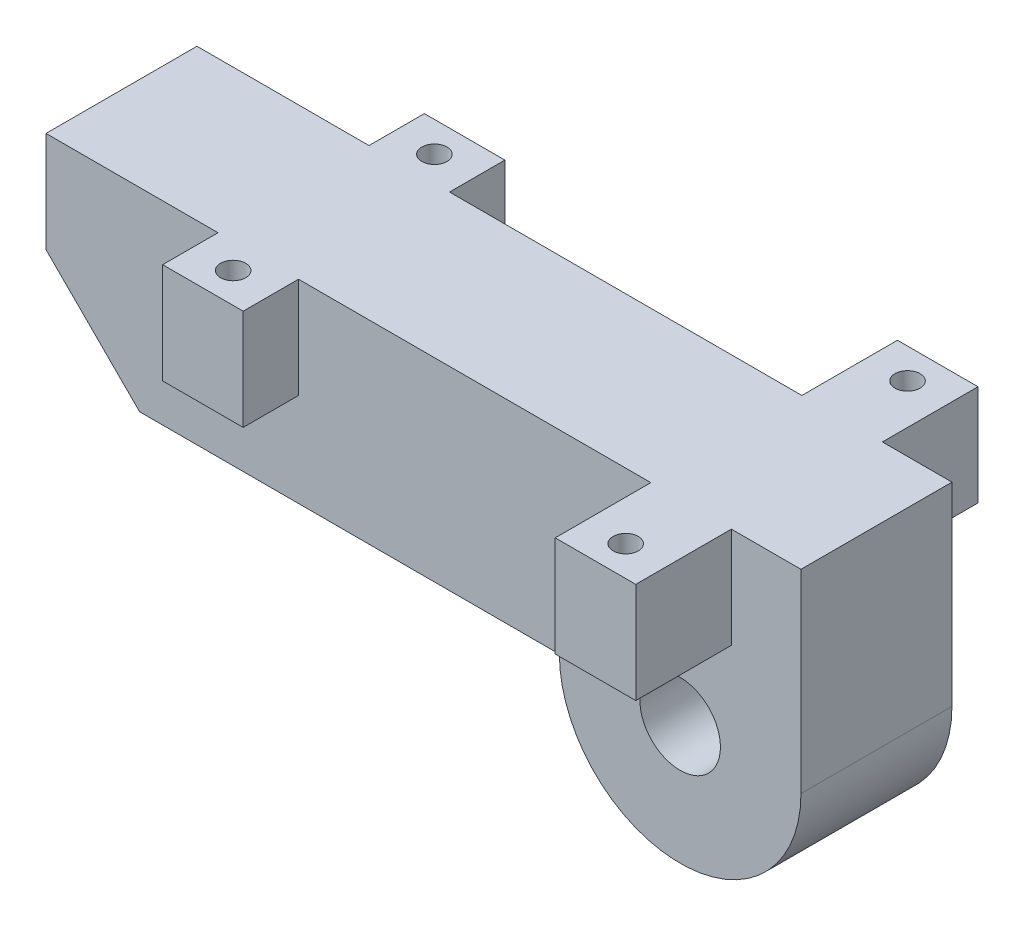
SolidWorks part; units mm, degrees
material "6061 合金"
ref_plane "前视基准面" through (0, 0, 0) normal (0, 0, 1) x (1, 0, 0)
ref_plane "上视基准面" through (0, 0, 0) normal (0, 1, 0) x (1, 0, 0)
ref_plane "右视基准面" through (0, 0, 0) normal (1, 0, 0) x (0, 0, -1)
sketch "草图2" plane through (0, 0, 0) normal (0, 1, 0) x (1, 0, 0)
  line L0 (-16.4121, -13) -> (-16.4121, 13) construction
  line L1 (37.5, 7.5) -> (30.5879, 7.5)
  line L2 (37.5, 7.5) -> (37.5, -7.5)
  line L3 (37.5, -7.5) -> (30.5879, -7.5)
  line L4 (-37.5, 7.5) -> (-37.5, -7.5)
  line L5 (37.5, 7.5) -> (-37.5, -7.5) construction
  line L6 (37.5, -7.5) -> (-37.5, 7.5) construction
  line L7 (-20.4121, 13) -> (-12.4121, 13)
  line L8 (-20.4121, 13) -> (-20.4121, 7.5)
  line L9 (-20.4121, -13) -> (-12.4121, -13)
  line L10 (-12.4121, 13) -> (-12.4121, 7.5)
  line L11 (22.5879, 17) -> (30.5879, 17)
  line L12 (22.5879, 17) -> (22.5879, 7.5)
  line L13 (22.5879, -17) -> (30.5879, -17)
  line L14 (30.5879, 17) -> (30.5879, 7.5)
  line L15 (-20.4121, -7.5) -> (-20.4121, -13)
  line L16 (-12.4121, -7.5) -> (-12.4121, -13)
  line L17 (-20.4121, -7.5) -> (-37.5, -7.5)
  line L18 (-20.4121, 7.5) -> (-37.5, 7.5)
  line L19 (22.5879, 7.5) -> (-12.4121, 7.5)
  line L20 (22.5879, -7.5) -> (22.5879, -17)
  line L21 (30.5879, -7.5) -> (30.5879, -17)
  line L22 (22.5879, -7.5) -> (-12.4121, -7.5)
  line L23 (-20.4121, 7.5) -> (-20.4121, -7.5) construction
  line L24 (-12.4121, 7.5) -> (-12.4121, -7.5) construction
  line L25 (22.5879, 7.5) -> (22.5879, -7.5) construction
  line L26 (30.5879, 7.5) -> (30.5879, -7.5) construction
  line L27 (-37.5, 0) -> (37.5, 0) construction
  line L28 (26.5879, 17) -> (26.5879, -17) construction
  point P0 (0, 0)
  point P24 (-16.4121, 10)
  point P29 (26.5879, 14)
  point P30 (0, 0)
  point P31 (-16.4121, -10)
  point P32 (26.5879, -14)
  dimension "D1" = 75
  dimension "D2" = 15
  dimension "D3" = 26
  dimension "D4" = 34
  dimension "D5" = 8
  dimension "D6" = 20
  dimension "D7" = 28
  dimension "D8" = 43
extrude "凸台-拉伸1" add sketch "草图2" along normal blind 10
hole_wizard "M3 螺纹孔1" positions "草图4" profile "草图5" tap size "M3" standard "GB" end condition through all
sketch "草图4" plane through (0, 10, 0) normal (0, 1, 0) x (1, 0, 0)
  point P0 (-16.4121, 10)
  point P3 (-16.4121, -10)
  point P6 (26.5879, 14)
  point P9 (26.5879, -14)
sketch "草图5" plane through (-16.4121, 10, -10) normal (1, 0, 0) x (0, 0, 1)
  line L0 (0, 0) -> (0, 10)
  line L1 (0, 10) -> (1.25, 10)
  line L2 (1.25, 10) -> (1.25, 0)
  line L5 (1.25, 0) -> (0, 0)
  line L11 (0, -6.35) -> (0, 107.95) construction
  dimension "通孔螺纹孔钻头直径" = 2.5
  dimension "通孔螺纹孔钻头深度" = 10
cosmetic thread "孔螺蚊线1" parameters "D2"=3
cosmetic thread "孔螺蚊线2" parameters "D2"=3
cosmetic thread "孔螺蚊线3" parameters "D2"=3
cosmetic thread "孔螺蚊线4" parameters "D2"=3
sketch "草图6" plane through (0, 0, 7.5) normal (0, 0, 1) x (1, 0, 0)
  line L0 (-37.5, 0) -> (37.5, 0)
  line L1 (-37.5, 0) -> (-28.2015, -9.2985)
  line L2 (-28.2015, -9.2985) -> (13.5, -9.2985)
  line L3 (37.5, 0) -> (37.5, -9.2985)
  arc A0 (13.5, -9.2985) -> (37.5, -9.2985) centre (25.5, -9.2985) ccw
  circle A1 centre (25.5, -9.2985) radius 4
  dimension "D1" = 12
  dimension "D2" = 8
extrude "凸台-拉伸2" add sketch "草图6" against normal up to surface (15 mm away) up to face at (34.0439, 5, -7.5)
